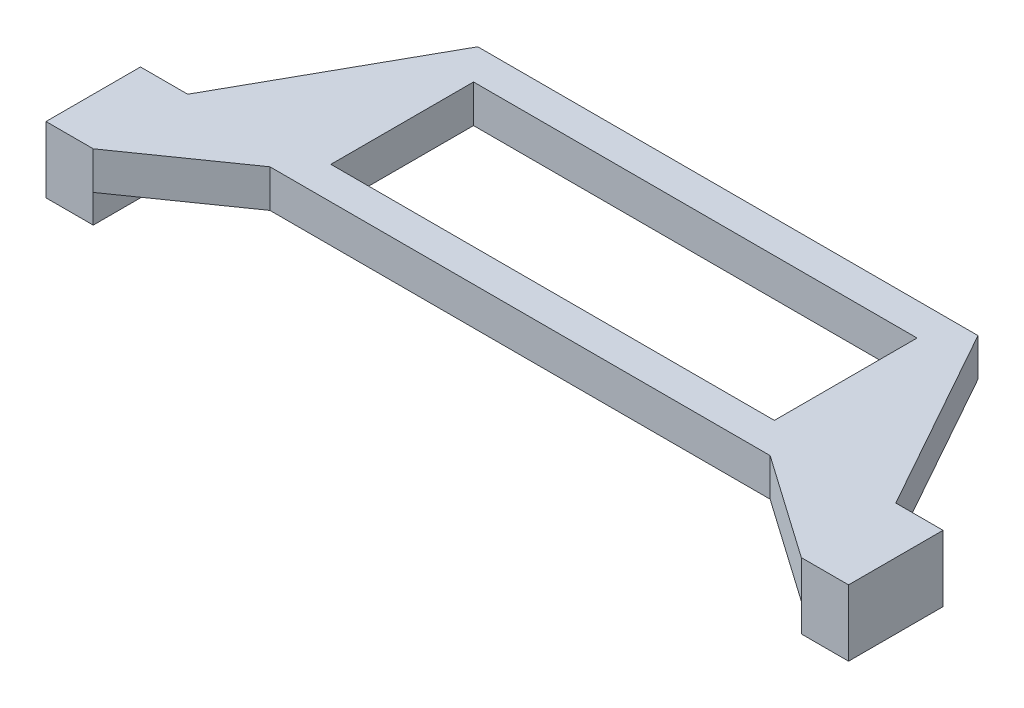
SolidWorks part; units mm, degrees
ref_plane "Front" through (0, 0, 0) normal (0, 0, 1) x (1, 0, 0)
ref_plane "Top" through (0, 0, 0) normal (0, 1, 0) x (1, 0, 0)
ref_plane "Right" through (0, 0, 0) normal (1, 0, 0) x (0, 0, -1)
sketch "Эскиз1" plane through (0, 0, 0) normal (0, 1, 0) x (1, 0, 0)
  line L0 (0, 23.7496) -> (0, -27.3712) construction
  line L2 (-42.47, 10) -> (-37.47, 10)
  line L3 (-42.47, 10) -> (-42.47, 0)
  line L4 (-42.47, 0) -> (-37.47, 0)
  line L5 (-37.47, 10) -> (-37.47, 0)
  line L6 (37.47, 10) -> (42.47, 10)
  line L7 (37.47, 10) -> (37.47, 0)
  line L8 (37.47, 0) -> (42.47, 0)
  line L9 (42.47, 10) -> (42.47, 0)
  dimension "D1" = 74.94
  dimension "D2" = 5
  dimension "D3" = 10
extrude "Бобышка-Вытянуть1" add sketch "Эскиз1" along normal blind 7
sketch "Эскиз2" plane through (0, 7, 0) normal (0, 1, 0) x (1, 0, 0)
  line L0 (26.47, 26.25) -> (-26.53, 26.25) construction
  line L1 (26.47, 29.7) -> (-26.47, 29.7)
  line L2 (26.47, 29.7) -> (26.47, 26.25)
  line L3 (26.47, 26.25) -> (-26.47, 26.25)
  line L4 (-26.47, 29.7) -> (-26.47, 26.25)
  line L5 (0, 0) -> (0, 79.552) construction
  line L6 (11.47, 29.7) -> (26.47, 29.7) construction
  line L7 (26.47, 11.15) -> (-26.47, 11.15)
  line L8 (26.47, 11.15) -> (26.47, 7.7)
  line L9 (26.47, 7.7) -> (-26.47, 7.7)
  line L10 (-26.47, 11.15) -> (-26.47, 7.7)
  line L11 (26.47, 7.7) -> (37.47, 0)
  line L12 (37.47, 10) -> (26.47, 29.7)
  line L13 (23.47, 26.25) -> (23.47, 11.15)
  line L14 (23.47, 11.15) -> (26.47, 11.15)
  line L15 (23.47, 26.25) -> (26.47, 26.25)
  line L16 (37.47, 0) -> (37.47, 10)
  line L17 (-26.47, 7.7) -> (-37.47, 0)
  line L18 (-26.47, 11.15) -> (-26.47, 7.7)
  line L19 (-23.47, 26.25) -> (-23.47, 11.15)
  line L20 (-26.47, 29.7) -> (-26.47, 26.25)
  line L21 (-37.47, 10) -> (-26.47, 29.7)
  line L22 (-37.47, 0) -> (-37.47, 10)
  line M13 (37.47, 10) -> (37.47, 0)
  dimension "D1" = 22
  dimension "D2" = 3
extrude "Бобышка-Вытянуть2" add sketch "Эскиз2" against normal blind 4 contours L3 L5 L1 L4 | L22 L17 L10 L7 L19 L3 L4 L21 | L5 L3 L2 L1 | L5 L9 L8 L7 | L9 L5 L7 L10 | L3 L13 L7 L8 L11 L12 L2 M13
